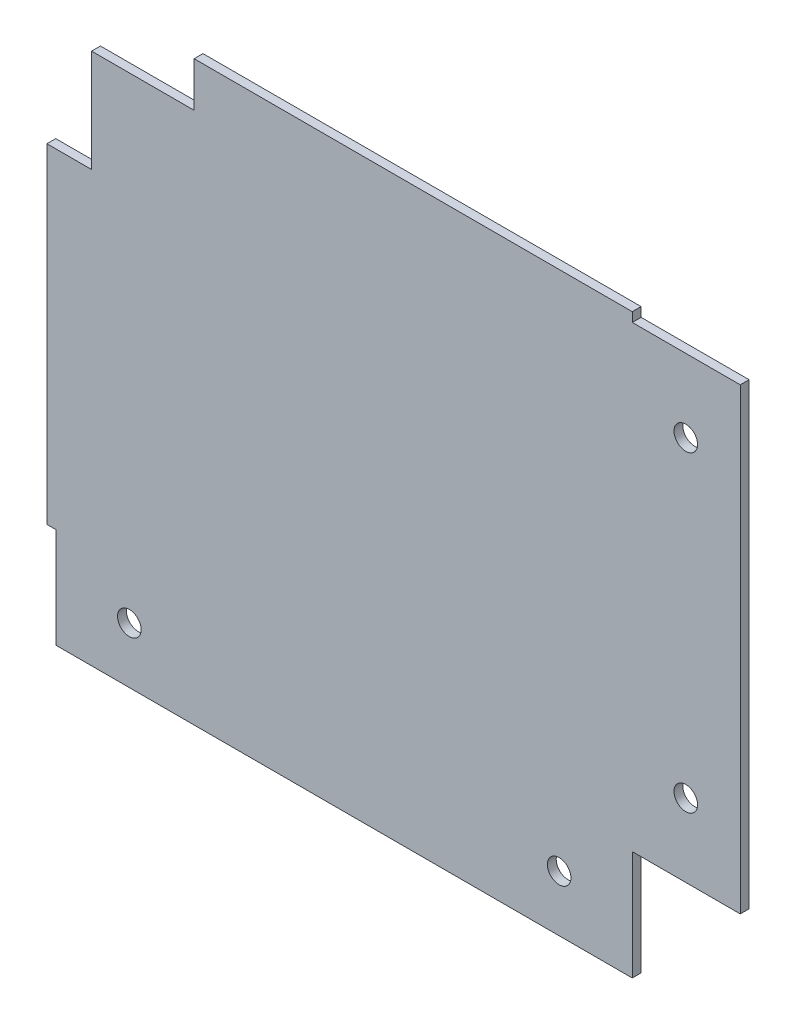
SolidWorks part; units mm, degrees
ref_plane "Front Plane" through (0, 0, 0) normal (0, 0, 1) x (1, 0, 0)
ref_plane "Top Plane" through (0, 0, 0) normal (0, 1, 0) x (1, 0, 0)
ref_plane "Right Plane" through (0, 0, 0) normal (1, 0, 0) x (0, 0, -1)
sketch "Sketch1" plane through (0, 0, 0) normal (0, 0, 1) x (1, 0, 0)
  line L0 (195.645, 0) -> (195.645, 37.18)
  line L1 (0, 0) -> (195.645, 0)
  line L3 (46.835, 196) -> (195.645, 196)
  line L5 (195.645, 37.18) -> (232.325, 37.18)
  line L6 (232.325, 37.18) -> (232.325, 192.825)
  line L7 (232.325, 192.825) -> (195.645, 192.825)
  line L8 (195.645, 192.825) -> (195.645, 196)
  line L9 (0, 0) -> (0, 34.005)
  line L11 (-3.175, 34.005) -> (-3.175, 145.99)
  line L12 (-3.175, 145.99) -> (12.005, 145.99)
  line L14 (46.835, 196) -> (46.835, 180.82)
  line L15 (46.835, 180.82) -> (12.005, 180.82)
  line L16 (12.005, 180.82) -> (12.005, 145.99)
  line L17 (-3.175, 34.005) -> (0, 34.005)
  circle A0 centre (170.815, 19.005) radius 4
  circle A1 centre (24.83, 19.005) radius 4
  circle A2 centre (213.82, 62.01) radius 4
  circle A3 centre (213.82, 167.995) radius 4
  point P21 (0, 0)
  point P22 (0, 0)
  dimension "D13" = 8
  dimension "D1" = 34.005
  dimension "D2" = 3.175
  dimension "D3" = 235.5
  dimension "D4" = 37.18
  dimension "D5" = 36.68
  dimension "D6" = 3.175
  dimension "D7" = 34.83
  dimension "D8" = 15.18
  dimension "D9" = 15.18
  dimension "D10" = 196
  dimension "D11" = 34.83
  dimension "D12" = 36.68
  dimension "D14" = 24.83
  dimension "D15" = 18.175
  dimension "D16" = 24.83
  dimension "D18" = 24.83
  dimension "D19" = 18.175
  dimension "D20" = 24.83
extrude "Boss-Extrude1" add sketch "Sketch1" along normal blind 3
